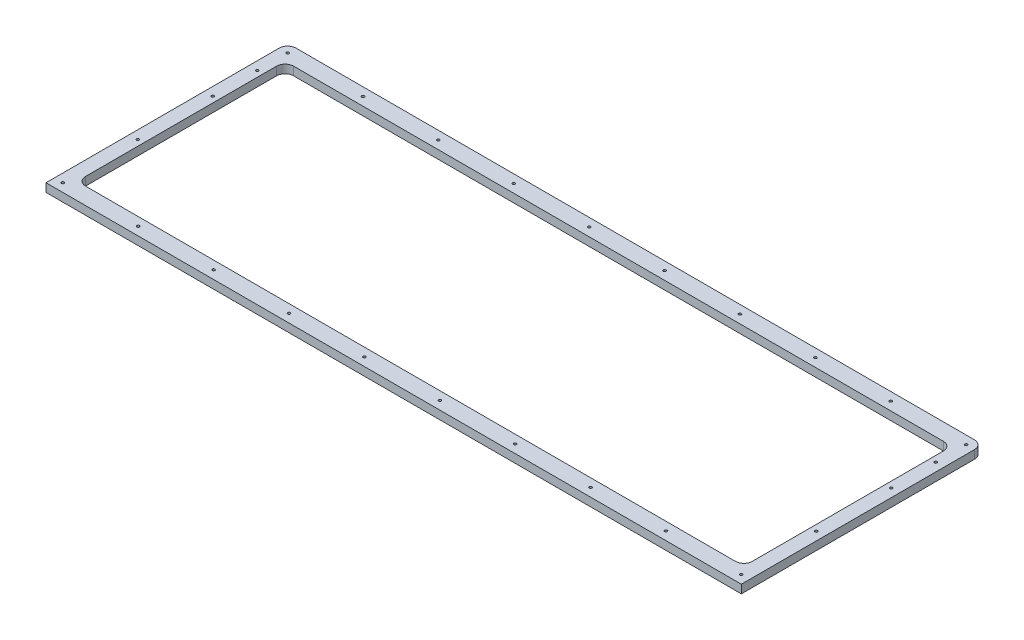
SolidWorks part; units mm, degrees
ref_plane "Płaszczyzna przednia" through (0, 0, 0) normal (0, 0, 1) x (1, 0, 0)
ref_plane "Płaszczyzna górna" through (0, 0, 0) normal (0, 1, 0) x (1, 0, 0)
ref_plane "Płaszczyzna prawa" through (0, 0, 0) normal (1, 0, 0) x (0, 0, -1)
sketch "Szkic2" plane through (0, 1505.9474, 0) normal (0, 1, 0) x (0, 0, 1)
  line L0 (-183.9552, 657.685) -> (-183.9552, -148.315)
  line L1 (-173.9552, 667.685) -> (103.0448, 667.685)
  line L2 (-173.9552, -158.315) -> (103.0448, -158.315)
  line L3 (103.0448, 667.685) -> (103.0448, -158.315)
  arc A0 (-173.9552, 667.685) -> (-183.9552, 657.685) centre (-173.9552, 657.685) ccw
  arc A1 (-183.9552, -148.315) -> (-173.9552, -158.315) centre (-173.9552, -148.315) ccw
  dimension "D3" = 10
  dimension "D4" = 10
  dimension "D1" = 826
  dimension "D2" = 287
extrude "Dodanie-wyciągnięcie1" add sketch "Szkic2" along normal blind 10
sketch "Szkic3" plane through (0, 1515.9474, 0) normal (0, 1, 0) x (1, 0, 0)
  line L0 (-158.315, 173.9552) -> (-158.315, -103.0448) construction
  line L1 (-158.315, -103.0448) -> (667.685, -103.0448) construction
  line L18 (650.685, -73.0448) -> (650.685, 153.9552)
  line L19 (-131.315, -83.0448) -> (640.685, -83.0448)
  line L20 (640.685, 163.9552) -> (-131.315, 163.9552)
  line L21 (-141.315, 153.9552) -> (-141.315, -73.0448)
  arc A0 (650.685, 153.9552) -> (640.685, 163.9552) centre (640.685, 153.9552) ccw
  arc A1 (650.685, -73.0448) -> (640.685, -83.0448) centre (640.685, -73.0448) cw
  arc A2 (-131.315, -83.0448) -> (-141.315, -73.0448) centre (-131.315, -73.0448) cw
  arc A3 (-131.315, 163.9552) -> (-141.315, 153.9552) centre (-131.315, 153.9552) ccw
  dimension "D2" = 10
  dimension "D1" = 792
  dimension "D3" = 17
  dimension "D4" = 247
  dimension "D5" = 20
extrude "Wytnij-wyciągnięcie1" cut sketch "Szkic3" against normal blind 10
sketch "Szkic4" plane through (0, 1515.9474, 0) normal (0, 1, 0) x (1, 0, 0)
  line L0 (640.685, 163.9552) -> (-131.315, 163.9552) construction
  line L2 (667.685, -103.0448) -> (667.685, 173.9552) construction
  circle A0 centre (657.685, 173.9552) radius 1.55
  dimension "D1" = 3.1
  dimension "D2" = 10
  dimension "D3" = 10
extrude "Wytnij-wyciągnięcie2" cut sketch "Szkic4" against normal blind 10
pattern_linear "Szyk liniowy1" count 9 spacing 89.555 along (-1, 0, 0) count 4 spacing 89 along (0, 0, 1) of "Wytnij-wyciągnięcie2"
sketch "Szkic6" plane through (0, 1515.9474, 0) normal (0, 1, 0) x (1, 0, 0)
  line L0 (-158.315, -103.0448) -> (667.685, -103.0448) construction
  line L1 (-158.315, 173.9552) -> (-158.315, -103.0448) construction
  circle A0 centre (-148.315, -93.0448) radius 1.55
  dimension "D1" = 10
  dimension "D2" = 10
  dimension "D3" = 3.1
extrude "Wytnij-wyciągnięcie3" cut sketch "Szkic6" against normal blind 10
pattern_linear "Szyk liniowy2" count 4 spacing 89 along (0, 0, -1) count 9 spacing 89.555 along (1, 0, 0) of "Wytnij-wyciągnięcie3"
pattern_linear "Szyk liniowy3" count 2 spacing 36 along (0, 0, 1) of "Wytnij-wyciągnięcie2"
pattern_linear "Szyk liniowy4" count 2 spacing 231 along (0, 0, -1) of "Wytnij-wyciągnięcie3"
equation "\"tolerancja_wpusy\"=0.2"
equation "\"dlugosc_wpustu_duzy\"=20"
equation "\"srednica_otworu_M3\"=3.1"
equation "\"szerokosc_nogi_T\"=3.1"
equation "\"dlugosc_T_30\"=11"
equation "\"grubosc_na_nakretke_kwadrat\"=2"
equation "\"szerokosc_na_nakretke_kwadrat\"=5.85"
equation "\"wyokosc_nadstawki_T\"=0.5"
equation "\"dlugosc_T_20_6\"=14"
equation "\"D1@Szkic4\"=\"srednica_otworu_M3\""
equation "\"D3@Szkic6\"=\"srednica_otworu_M3\""
